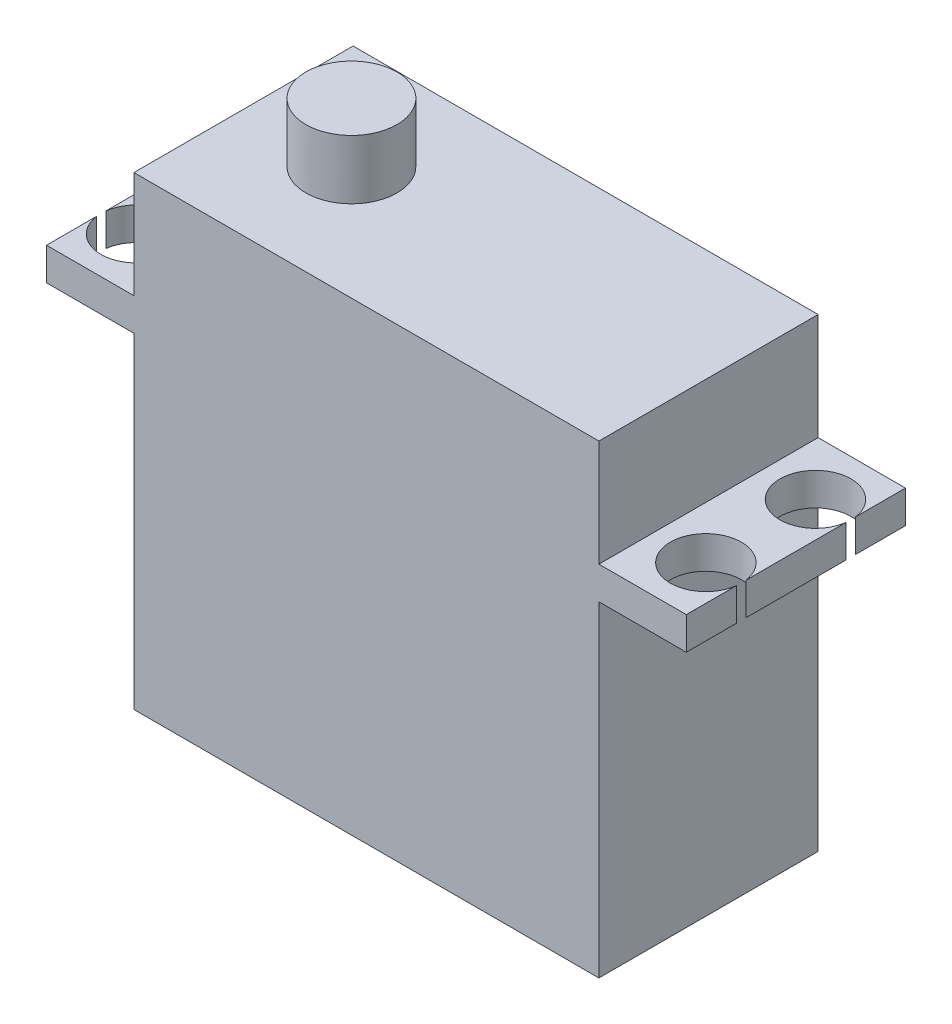
SolidWorks part; units mm, degrees
ref_plane "Front Plane" through (0, 0, 0) normal (0, 0, 1) x (1, 0, 0)
ref_plane "Top Plane" through (0, 0, 0) normal (0, 1, 0) x (1, 0, 0)
ref_plane "Right Plane" through (0, 0, 0) normal (1, 0, 0) x (0, 0, -1)
sketch "Sketch1" plane through (0, 0, 0) normal (0, 1, 0) x (1, 0, 0)
  line L1 (0, 0) -> (39.878, 0)
  line L2 (0, 0) -> (0, 18.796)
  line L3 (0, 18.796) -> (39.878, 18.796)
  line L4 (39.878, 0) -> (39.878, 18.796)
  dimension "D1" = 39.878
  dimension "D2" = 18.796
extrude "Boss-Extrude1" add sketch "Sketch1" along normal blind 39.878
sketch "Sketch2" plane through (0, 0, 0) normal (-1, 0, 0) x (0, 0, 1)
  line L0 (-18.796, 0) -> (-18.796, 27.94) construction
  line L1 (-18.796, 39.878) -> (-18.796, 0) construction
  line L13 (0, 39.878) -> (0, 0) construction
  line L14 (-18.796, 27.94) -> (0, 27.94)
  line L15 (-18.796, 27.94) -> (-18.796, 30.734)
  line L16 (-18.796, 30.734) -> (0, 30.734)
  line L17 (0, 27.94) -> (0, 30.734)
  dimension "D1" = 2.794
extrude "Boss-Extrude2" add sketch "Sketch2" along normal blind 7.493
sketch "Sketch3" plane through (39.878, 0, 0) normal (1, 0, 0) x (0, 0, -1)
  line L0 (0, 0) -> (0, 27.94) construction
  line L6 (0, 39.878) -> (0, 0) construction
  line L8 (0, 27.94) -> (18.796, 27.94)
  line L9 (0, 27.94) -> (0, 30.734)
  line L10 (0, 30.734) -> (18.796, 30.734)
  line L11 (18.796, 27.94) -> (18.796, 30.734)
  dimension "D1" = 2.794
extrude "Boss-Extrude3" add sketch "Sketch3" along normal blind 7.493
sketch "Sketch5" plane through (0, 0, 0) normal (-1, 0, 0) x (0, 0, 1)
  line L0 (-18.796, 0) -> (0, 0) construction
  line L1 (-13.0375, 0) -> (-6.492, 0)
  line L2 (-13.0375, 0) -> (-13.0375, 4.8116)
  line L3 (-13.0375, 4.8116) -> (-6.492, 4.8116)
  line L4 (-6.492, 0) -> (-6.492, 4.8116)
sketch "Sketch6" plane through (0, 39.878, 0) normal (0, 1, 0) x (1, 0, 0)
  line L0 (0, 9.7648) -> (8.89, 9.7648) construction
  line L1 (0, 13.0375) -> (0, 6.492) construction
  circle A0 centre (8.89, 9.7648) radius 3.9081
extrude "Boss-Extrude5" add sketch "Sketch6" along normal blind 5.08
sketch "Sketch7" plane through (0, 30.734, 0) normal (0, 1, 0) x (1, 0, 0)
  line L0 (-7.493, 9.398) -> (-7.493, 18.796) construction
  line L1 (-7.493, 0) -> (-7.493, 18.796) construction
  line L2 (-7.493, 9.398) -> (0, 9.398) construction
  line L3 (-7.493, 14.097) -> (-4.4715, 14.097) construction
  line L4 (0, 13.0375) -> (0, 6.492) construction
  line L5 (19.939, 18.796) -> (19.939, 0) construction
  line L6 (39.878, 18.796) -> (0, 18.796) construction
  line L7 (0, 0) -> (39.878, 0) construction
  circle A0 centre (-4.4715, 14.097) radius 3.048
  circle A1 centre (-4.4715, 4.699) radius 3.048
  circle A2 centre (44.3495, 4.699) radius 3.048
  circle A3 centre (44.3495, 14.097) radius 3.048
extrude "Cut-Extrude1" cut sketch "Sketch7" against normal blind 5.08
